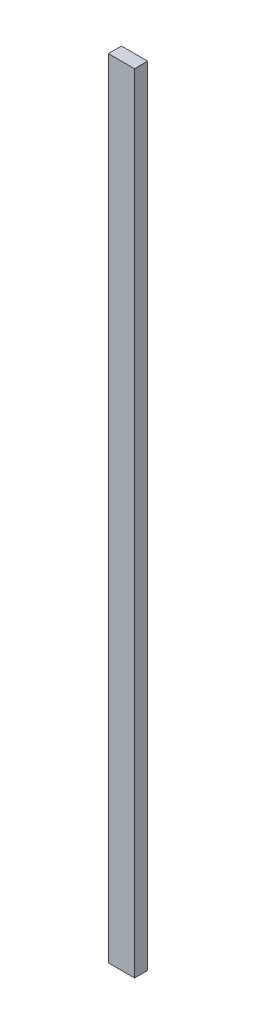
SolidWorks part; units mm, degrees
ref_plane "Plan de face" through (0, 0, 0) normal (0, 0, 1) x (1, 0, 0)
ref_plane "Plan de dessus" through (0, 0, 0) normal (0, 1, 0) x (1, 0, 0)
ref_plane "Plan de droite" through (0, 0, 0) normal (1, 0, 0) x (0, 0, -1)
sketch "Esquisse1" plane through (0, 0, 0) normal (0, 0, 1) x (1, 0, 0)
  line L1 (0, 0) -> (20, 0)
  line L2 (0, 0) -> (0, 600)
  line L3 (0, 600) -> (20, 600)
  line L4 (20, 0) -> (20, 600)
  dimension "D1" = 20
  dimension "D2" = 600
extrude "Boss.-Extru.1" add sketch "Esquisse1" along normal blind 10
